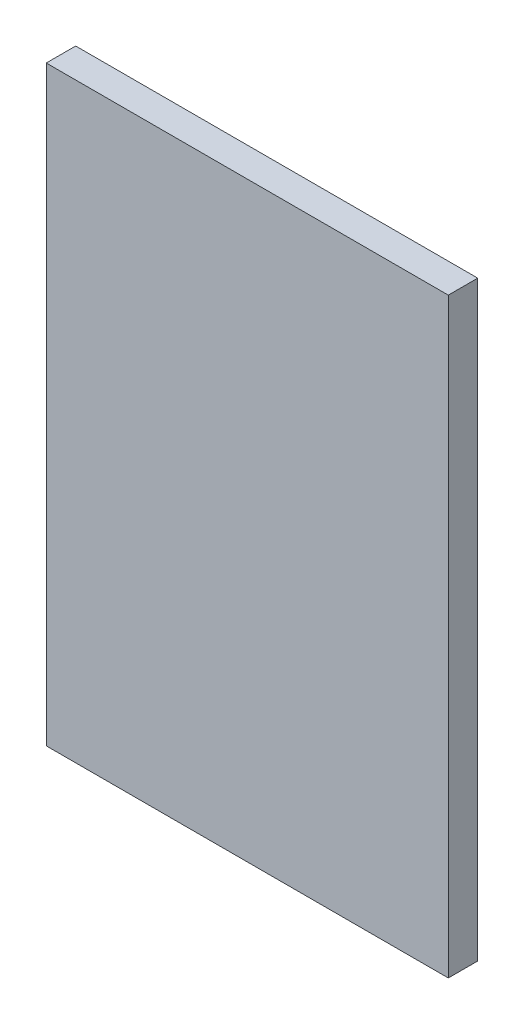
SolidWorks part; units mm, degrees
ref_plane "Front Plane" through (0, 0, 0) normal (0, 0, 1) x (1, 0, 0)
ref_plane "Top Plane" through (0, 0, 0) normal (0, 1, 0) x (1, 0, 0)
ref_plane "Right Plane" through (0, 0, 0) normal (1, 0, 0) x (0, 0, -1)
sketch "Sketch1" plane through (0, 0, 0) normal (0, 0, 1) x (1, 0, 0)
  line L1 (-34.6931, -51.0306) -> (34.6931, -51.0306)
  line L2 (-34.6931, -51.0306) -> (-34.6931, 51.0306)
  line L3 (-34.6931, 51.0306) -> (34.6931, 51.0306)
  line L4 (34.6931, -51.0306) -> (34.6931, 51.0306)
  line L5 (-34.6931, -51.0306) -> (34.6931, 51.0306) construction
  line L6 (-34.6931, 51.0306) -> (34.6931, -51.0306) construction
  point P0 (0, 0)
extrude "Extrude1" add sketch "Sketch1" along normal blind 5.08
sketch "Sketch2" plane through (0, 0, 5.08) normal (0, 0, 1) x (1, 0, 0)
  line L0 (0, 51.0306) -> (0, 29.918) construction
  line L1 (34.6931, 51.0306) -> (-34.6931, 51.0306) construction
  line L2 (0, -51.0306) -> (0, -29.918) construction
  line L3 (-34.6931, -51.0306) -> (34.6931, -51.0306) construction
